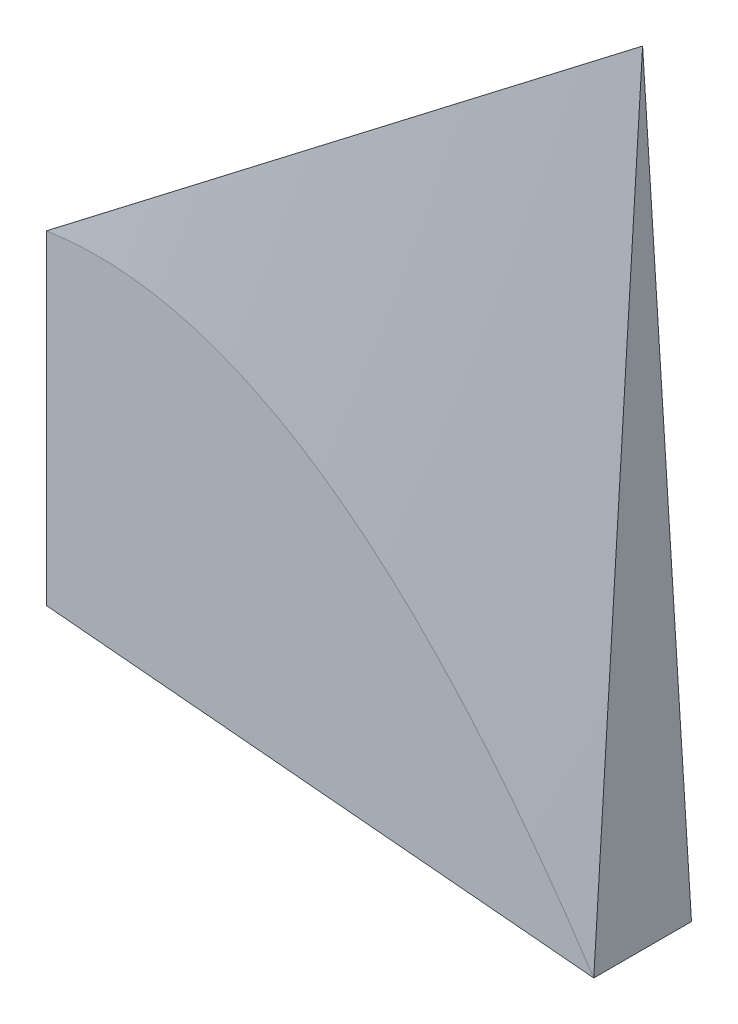
SolidWorks part; units mm, degrees
ref_plane "Front Plane" through (0, 0, 0) normal (0, 0, 1) x (1, 0, 0)
ref_plane "Top Plane" through (0, 0, 0) normal (0, 1, 0) x (1, 0, 0)
ref_plane "Right Plane" through (0, 0, 0) normal (1, 0, 0) x (0, 0, -1)
sketch "Sketch6" plane through (0, 0, 0) normal (0, 0, 1) x (1, 0, 0)
  line L0 (-58.3899, 209.0102) -> (-58.3899, 129.0102)
  line L1 (-58.3899, 129.0102) -> (-118.3899, 129.0102)
  line L2 (-118.3899, 129.0102) -> (-118.3899, 159.0102)
  line L3 (-118.3899, 159.0102) -> (-58.3899, 209.0102)
sketch3d "3DSketch1" plane through (0, 0, 0) normal (0, 0, 1) x (1, 0, 0)
sketch "Sketch10" plane through (-57.3899, 0, 0) normal (1, 0, 0) x (0, 0, -1)
  line L0 (-5, 129.0102) -> (0, 209.1064)
  line L1 (0, 209.1064) -> (5, 129.0102)
  line L2 (5, 129.0102) -> (-5, 129.0102)
sketch "Sketch11" plane through (-118.3899, 0, 0) normal (1, 0, 0) x (0, 0, -1)
  line L0 (-5, 129.0102) -> (0, 162.2293)
  line L1 (0, 162.2293) -> (5, 129.0102)
  line L2 (5, 129.0102) -> (-5, 129.0102)
loft "Loft1" add profiles "Sketch11", "Sketch10"
sketch "Sketch12" plane through (0, 129.0102, 0) normal (0, -1, 0) x (1, 0, 0)
  line L0 (-57.3899, -5) -> (-118.3899, 0)
  line L1 (-118.3899, 0) -> (-58.3899, 0) construction
  line L2 (-58.3899, 0) -> (-118.3899, 0) construction
  line L3 (-118.3899, 0) -> (-57.3899, 5)
  line L4 (-57.3899, 5) -> (-57.3899, -5)
extrude "Cut-Extrude2" cut sketch "Sketch12" against normal up to next (64.4706 mm away) flip side to cut
